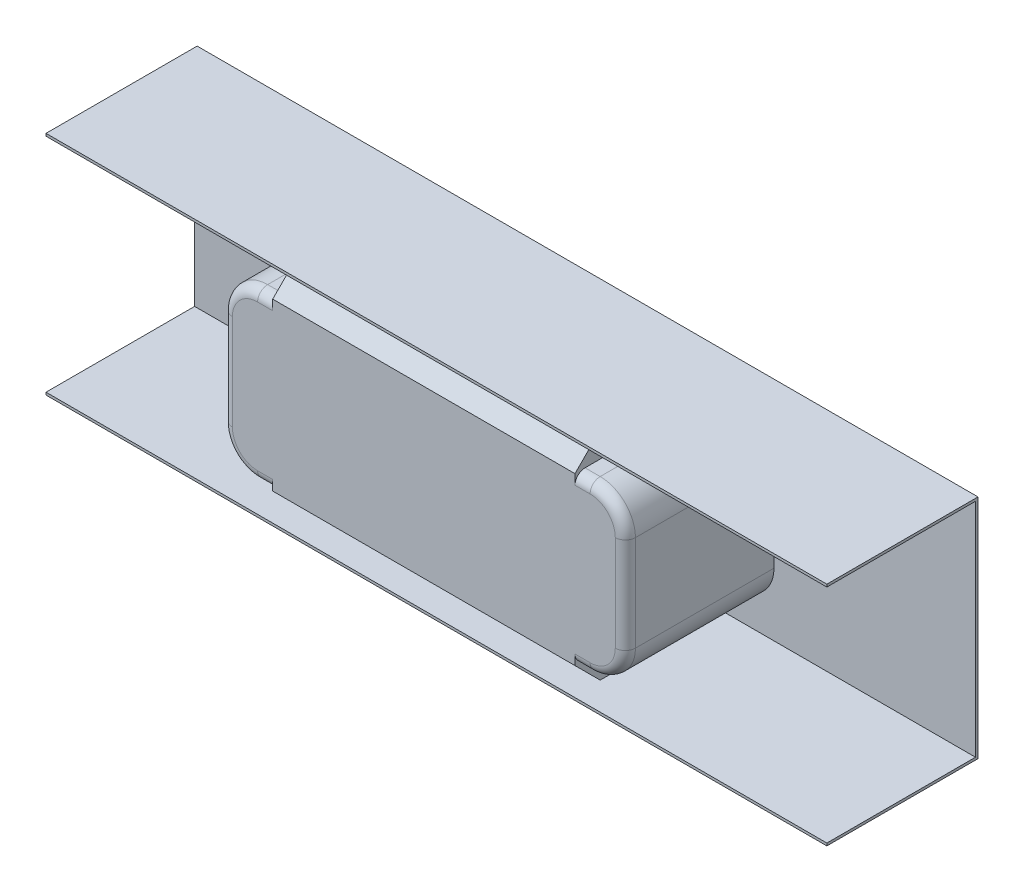
SolidWorks part; units mm, degrees
ref_plane "Спереди" through (0, 0, 0) normal (0, 0, 1) x (1, 0, 0)
ref_plane "Сверху" through (0, 0, 0) normal (0, 1, 0) x (1, 0, 0)
ref_plane "Справа" through (0, 0, 0) normal (1, 0, 0) x (0, 0, -1)
sketch "Sketch1" plane through (0, 0, 0) normal (0, 0, 1) x (1, 0, 0)
  line L1 (-34.1969, 24.4993) -> (115.8031, 24.4993)
  line L2 (-34.1969, 24.4993) -> (-34.1969, -20.5007)
  line L3 (-34.1969, -20.5007) -> (115.8031, -20.5007)
  line L4 (115.8031, 24.4993) -> (115.8031, -20.5007)
  dimension "D1" = 150
  dimension "D2" = 45
extrude "Extrude1" add sketch "Sketch1" along normal blind 30
sketch "Sketch2" plane through (0, 0, 30) normal (0, 0, 1) x (1, 0, 0)
  line L0 (70.8031, -19.5007) -> (70.8031, -14.5007)
  line L1 (70.8031, -14.5007) -> (73.8031, -14.5007)
  line L2 (80.8031, -7.5007) -> (80.8031, 11.4993)
  line L3 (73.8031, 18.4993) -> (70.8031, 18.4993)
  line L4 (-34.1969, 24.4993) -> (-34.1969, -20.5007)
  line L5 (-34.1969, -20.5007) -> (115.8031, -20.5007)
  line L6 (115.8031, -20.5007) -> (115.8031, 24.4993)
  line L7 (115.8031, 24.4993) -> (-34.1969, 24.4993)
  line L8 (-34.1969, 23.9993) -> (-34.1969, -20.0007)
  line L9 (-34.1969, -20.5007) -> (10.8031, -20.5007) construction
  line L10 (115.8031, -20.0007) -> (115.8031, 23.9993)
  line L11 (115.8031, 24.4993) -> (-34.1969, 24.4993) construction
  line L12 (70.8031, 18.4993) -> (70.8031, 23.4993)
  line L13 (115.8031, 1.9993) -> (-34.1969, 1.9993) construction
  line L14 (40.8031, 24.4993) -> (40.8031, -20.5007) construction
  line L15 (73.8031, 11.4993) -> (73.8031, 1.9993) construction
  line L16 (73.8031, 1.9993) -> (73.8031, -7.5007) construction
  line L17 (10.8031, 18.4993) -> (10.8031, 23.4993)
  line L18 (7.8031, 18.4993) -> (10.8031, 18.4993)
  line L19 (0.8031, -7.5007) -> (0.8031, 11.4993)
  line L20 (10.8031, -14.5007) -> (7.8031, -14.5007)
  line L21 (10.8031, -19.5007) -> (10.8031, -14.5007)
  line L22 (-33.6969, 23.9993) -> (-33.6969, -20.0007) construction
  line L23 (-33.6969, -20.0007) -> (10.8031, -20.0007)
  line L24 (115.3031, -20.0007) -> (115.3031, 23.9993) construction
  line L25 (115.3031, 23.9993) -> (70.8031, 23.9993)
  line L26 (-33.6969, 23.9993) -> (-34.1969, 23.9993)
  line L27 (-33.6969, -20.0007) -> (-34.1969, -20.0007)
  line L28 (115.3031, -20.0007) -> (115.8031, -20.0007)
  line L29 (115.3031, 23.9993) -> (115.8031, 23.9993)
  line L30 (70.8031, -20.0007) -> (115.3031, -20.0007)
  line L31 (-33.6969, -20.0007) -> (115.3031, -20.0007) construction
  line L32 (70.8031, -20.5007) -> (115.8031, -20.5007) construction
  line L33 (-34.1969, -20.5007) -> (115.8031, -20.5007) construction
  line L34 (-34.1969, 24.4993) -> (-34.1969, -20.5007) construction
  line L35 (10.8031, 23.9993) -> (-33.6969, 23.9993)
  line L36 (115.3031, 23.9993) -> (-33.6969, 23.9993) construction
  line L37 (115.8031, -20.5007) -> (115.8031, 24.4993) construction
  line L38 (10.8031, 23.9993) -> (70.8031, 23.9993)
  line L40 (10.8031, 23.4993) -> (70.8031, 23.4993)
  line L41 (10.8031, -20.0007) -> (70.8031, -20.0007)
  line L42 (70.8031, -19.5007) -> (10.8031, -19.5007)
  arc A0 (73.8031, -14.5007) -> (80.8031, -7.5007) centre (73.8031, -7.5007) ccw
  arc A1 (80.8031, 11.4993) -> (73.8031, 18.4993) centre (73.8031, 11.4993) ccw
  arc A2 (0.8031, 11.4993) -> (7.8031, 18.4993) centre (7.8031, 11.4993) cw
  arc A3 (7.8031, -14.5007) -> (0.8031, -7.5007) centre (7.8031, -7.5007) cw
  dimension "D4" = 7
  dimension "D2" = 45
  dimension "D3" = 35
  dimension "D5" = 6
  dimension "D7" = 0.5
  dimension "D8" = 0.5
  dimension "D1" = 0
  dimension "D6" = 0.5
extrude "Cut-Extrude1" cut sketch "Sketch2" against normal offset from surface (29.5 mm away) 0.5 up to face at (40.8031, 1.9993, 0)
fillet "Fillet1" radius 2 10 edges at (9.3031, 18.4993, 30) (2.8533, 16.449, 30) (0.8031, 1.9993, 30) (2.8533, -12.4505, 30) (72.3031, -14.5007, 30) (78.7528, -12.4505, 30) (80.8031, 1.9993, 30) (78.7528, 16.449, 30) (9.3031, -14.5007, 30) (72.3031, 18.4993, 30)
chamfer "Chamfer1" distance 5 angle 45 2 edges at (40.8031, -19.5007, 30) (40.8031, 23.4993, 30)
sketch "Croquis1" plane through (115.8031, 0, 0) normal (1, 0, 0) x (0, 0, -1)
  line L8 (-0.5, 23.9993) -> (-0.5, -20.0007)
  line L9 (-0.5, -20.0007) -> (-30, -20.0007)
  line L10 (-30, -20.0007) -> (-30, -20.5007)
  line L11 (-30, -20.5007) -> (0, -20.5007)
  line L12 (0, -20.5007) -> (0, 24.4993)
  line L13 (0, 24.4993) -> (-30, 24.4993)
  line L14 (-30, 24.4993) -> (-30, 23.9993)
  line L15 (-30, 23.9993) -> (-0.5, 23.9993)
  line L16 (-0.5, 23.9993) -> (-0.5, -20.0007)
  line L17 (-0.5, -20.0007) -> (-30, -20.0007)
  line L18 (-30, -20.0007) -> (-30, -20.5007)
  line L19 (-30, -20.5007) -> (0, -20.5007)
  line L20 (0, -20.5007) -> (0, 24.4993)
  line L21 (0, 24.4993) -> (-30, 24.4993)
  line L22 (-30, 24.4993) -> (-30, 23.9993)
  line L23 (-30, 23.9993) -> (-0.5, 23.9993)
  dimension "D1" = 0
extrude "Saliente-Extruir1" add sketch "Croquis1" along normal blind 5
